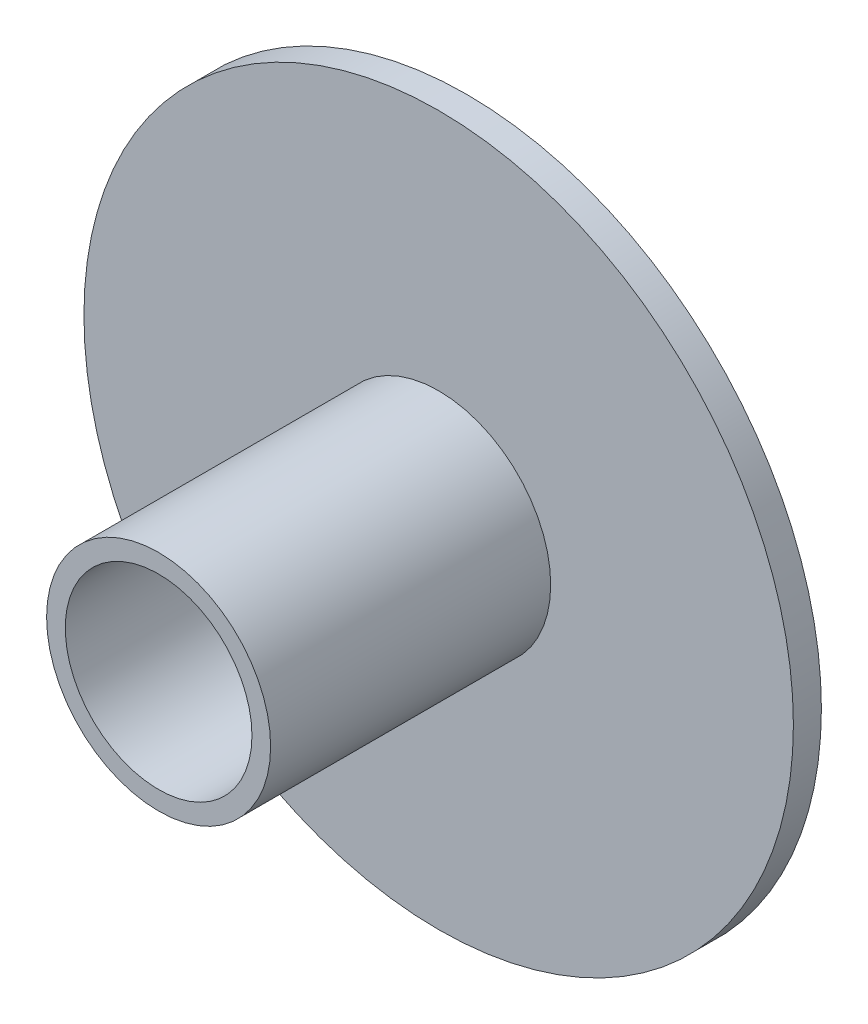
SolidWorks part; units mm, degrees
ref_plane "Front" through (0, 0, 0) normal (0, 0, 1) x (1, 0, 0)
ref_plane "Top" through (0, 0, 0) normal (0, 1, 0) x (1, 0, 0)
ref_plane "Right" through (0, 0, 0) normal (1, 0, 0) x (0, 0, -1)
sketch "Sketch1" plane through (0, 0, 0) normal (0, 0, 1) x (1, 0, 0)
  circle A0 centre (0, 0) radius 17.5 construction
  circle A1 centre (0, 0) radius 19
  dimension "D1" = 35
  dimension "D2" = 1.5
extrude "Boss-Extrude1" add sketch "Sketch1" along normal blind 1.5 contours A1
sketch "Sketch2" plane through (0, 0, 1.5) normal (0, 0, 1) x (1, 0, 0)
  circle A0 centre (0, 0) radius 5 construction
  circle A1 centre (0, 0) radius 6
  dimension "D1" = 10
  dimension "D2" = 1
extrude "Boss-Extrude2" add sketch "Sketch2" along normal blind 15
sketch "Sketch3" plane through (0, 0, 16.5) normal (0, 0, 1) x (1, 0, 0)
  circle A0 centre (0, 0) radius 5
  dimension "D1" = 10
extrude "Cut-Extrude1" cut sketch "Sketch3" against normal through all both and the other way through all contours A0
equation "\"D1@Sketch1\"=\"Cavity_Diameter\""
equation "\"Wall_Thickness\"= 1.5"
equation "\"Cavity_Diameter\"= 35"
equation "\"D2@Sketch1\"=\"Wall_Thickness\""
equation "\"D1@Boss-Extrude1\"=\"Wall_Thickness\""
equation "\"Outlet_Diameter\"= 10"
equation "\"D1@Sketch2\"=\"Outlet_Diameter\""
equation "\"Outlet_Length\"= 15"
equation "\"D1@Boss-Extrude2\"=\"Outlet_Length\""
equation "\"D1@Sketch3\"=\"Outlet_Diameter\""
